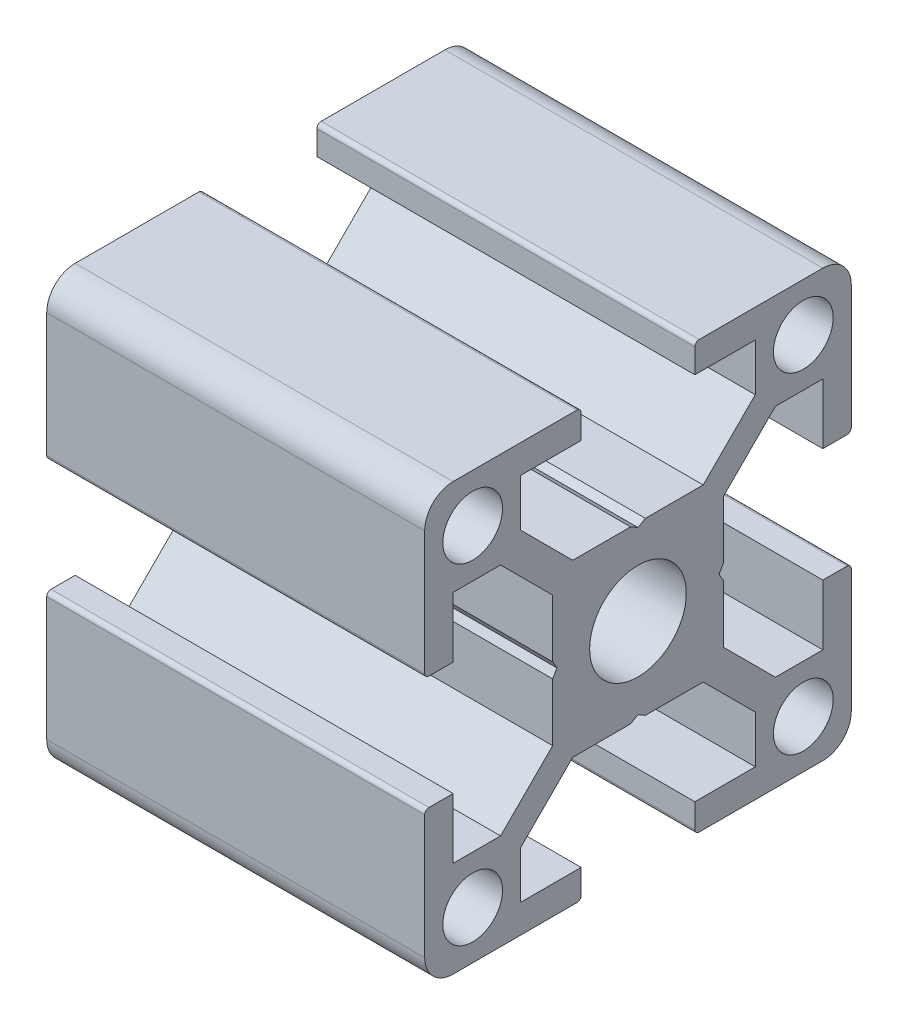
SolidWorks part; units mm, degrees
ref_plane "Front Plane" through (0, 0, 0) normal (0, 0, 1) x (1, 0, 0)
ref_plane "Top Plane" through (0, 0, 0) normal (0, 1, 0) x (1, 0, 0)
ref_plane "Right Plane" through (0, 0, 0) normal (1, 0, 0) x (0, 0, -1)
sketch "Sketch1" plane through (0, 0, 0) normal (0, 0, 1) x (1, 0, 0)
  line L0 (0, 0) -> (26.58, 0)
  dimension "D1" = 26.58
other "30xs6 30X30S6(1)"
ref_plane "Plane1" through (0, 0, 0) normal (1, 0, 0) x (0, 1, 0)
sketch "草图1" plane through (0, 0, 0) normal (1, 0, 0) x (0, 1, 0)
  line L0 (-14.7, 4) -> (-13, 4)
  line L1 (-13, 4) -> (-13, 8.25)
  line L2 (-13, 8.25) -> (-9.6642, 8.25)
  line L3 (-9.6642, 8.25) -> (-6, 4.5858)
  line L4 (-6, 4.5858) -> (-6, 0.5196)
  line L5 (-6, 0.5196) -> (-5.7, 0)
  line L6 (-5.7, 0) -> (-6, -0.5196)
  line L7 (-6, -0.5196) -> (-6, -4.5858)
  line L8 (-6, -4.5858) -> (-9.6642, -8.25)
  line L9 (-9.6642, -8.25) -> (-13, -8.25)
  line L10 (-13, -8.25) -> (-13, -4)
  line L11 (-13, -4) -> (-14.7, -4)
  line L12 (-15, -4.3) -> (-15, -13)
  line L13 (-13, -15) -> (-4.3, -15)
  line L14 (-4, -14.7) -> (-4, -13)
  line L15 (-4, -13) -> (-8.25, -13)
  line L16 (-8.25, -13) -> (-8.25, -9.6642)
  line L17 (-8.25, -9.6642) -> (-4.5858, -6)
  line L18 (-4.5858, -6) -> (-0.5196, -6)
  line L19 (-0.5196, -6) -> (0, -5.7)
  line L20 (0, -5.7) -> (0.5196, -6)
  line L21 (0.5196, -6) -> (4.5858, -6)
  line L22 (4.5858, -6) -> (8.25, -9.6642)
  line L23 (8.25, -9.6642) -> (8.25, -13)
  line L24 (8.25, -13) -> (4, -13)
  line L25 (4, -13) -> (4, -14.7)
  line L26 (4.3, -15) -> (13, -15)
  line L27 (15, -13) -> (15, -4.3)
  line L28 (14.7, -4) -> (13, -4)
  line L29 (13, -4) -> (13, -8.25)
  line L30 (13, -8.25) -> (9.6642, -8.25)
  line L31 (9.6642, -8.25) -> (6, -4.5858)
  line L32 (6, -4.5858) -> (6, -0.5196)
  line L33 (6, -0.5196) -> (5.7, 0)
  line L34 (5.7, 0) -> (6, 0.5196)
  line L35 (6, 0.5196) -> (6, 4.5858)
  line L36 (6, 4.5858) -> (9.6642, 8.25)
  line L37 (9.6642, 8.25) -> (13, 8.25)
  line L38 (13, 8.25) -> (13, 4)
  line L39 (13, 4) -> (14.7, 4)
  line L40 (15, 4.3) -> (15, 13)
  line L41 (13, 15) -> (4.3, 15)
  line L42 (4, 14.7) -> (4, 13)
  line L43 (4, 13) -> (8.25, 13)
  line L44 (8.25, 13) -> (8.25, 9.6642)
  line L45 (8.25, 9.6642) -> (4.5858, 6)
  line L46 (4.5858, 6) -> (0.5196, 6)
  line L47 (0.5196, 6) -> (0, 5.7)
  line L48 (0, 5.7) -> (-0.5196, 6)
  line L49 (-0.5196, 6) -> (-4.5858, 6)
  line L50 (-4.5858, 6) -> (-8.25, 9.6642)
  line L51 (-8.25, 9.6642) -> (-8.25, 13)
  line L52 (-8.25, 13) -> (-4, 13)
  line L53 (-4, 13) -> (-4, 14.7)
  line L54 (-4.3, 15) -> (-13, 15)
  line L55 (-15, 13) -> (-15, 4.3)
  arc A0 (-15, 4.3) -> (-14.7, 4) centre (-14.7, 4.3) ccw
  arc A1 (-14.7, -4) -> (-15, -4.3) centre (-14.7, -4.3) ccw
  arc A2 (-15, -13) -> (-13, -15) centre (-13, -13) ccw
  arc A3 (-4.3, -15) -> (-4, -14.7) centre (-4.3, -14.7) ccw
  arc A4 (4, -14.7) -> (4.3, -15) centre (4.3, -14.7) ccw
  arc A5 (13, -15) -> (15, -13) centre (13, -13) ccw
  arc A6 (15, -4.3) -> (14.7, -4) centre (14.7, -4.3) ccw
  arc A7 (14.7, 4) -> (15, 4.3) centre (14.7, 4.3) ccw
  arc A8 (15, 13) -> (13, 15) centre (13, 13) ccw
  arc A9 (4.3, 15) -> (4, 14.7) centre (4.3, 14.7) ccw
  arc A10 (-4, 14.7) -> (-4.3, 15) centre (-4.3, 14.7) ccw
  arc A11 (-13, 15) -> (-15, 13) centre (-13, 13) ccw
  circle A12 centre (11.625, 11.625) radius 2.1
  circle A13 centre (11.625, -11.625) radius 2.1
  circle A14 centre (0, 0) radius 3.4
  circle A15 centre (-11.625, -11.625) radius 2.1
  circle A16 centre (-11.625, 11.625) radius 2.1
  point P90 (-15, 15)
  point P91 (-0.2598, 14.9121)
  point P92 (15, 15)
  point P93 (15, 0)
  point P94 (15, -15)
  point P95 (0.2598, -15)
  point P96 (-15, -15)
  point P97 (-15, 0)
  point P98 (0, 0)
